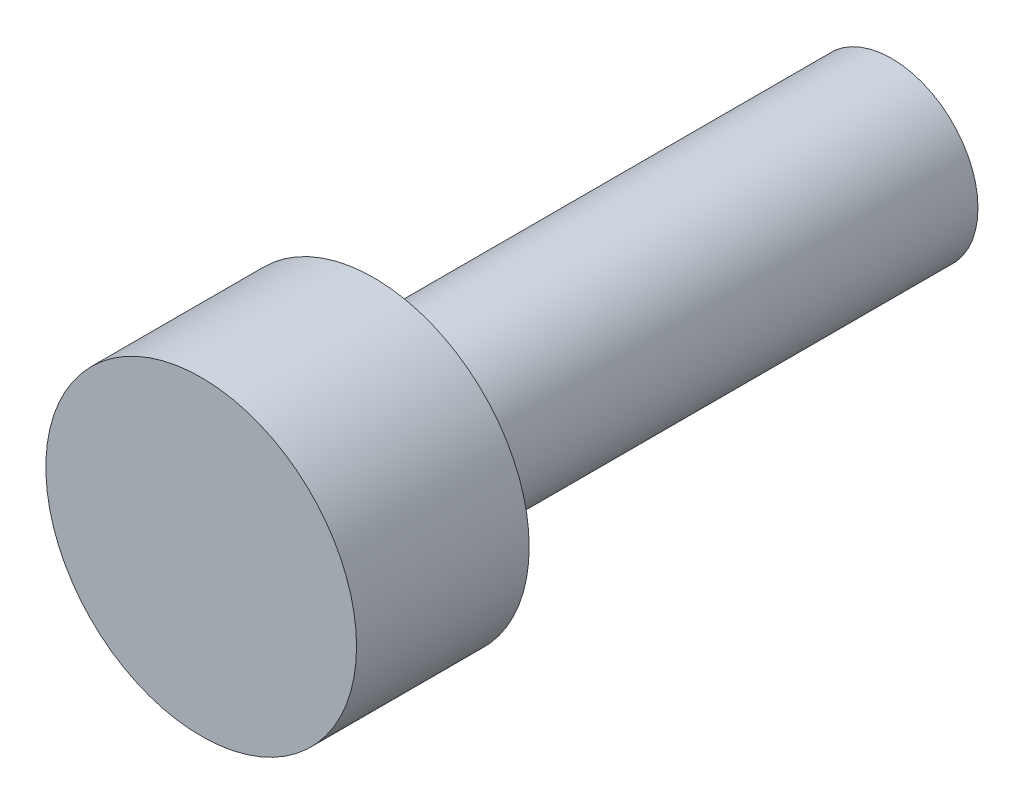
SolidWorks part; units mm, degrees
ref_plane "前视基准面" through (0, 0, 0) normal (0, 0, 1) x (1, 0, 0)
ref_plane "上视基准面" through (0, 0, 0) normal (0, 1, 0) x (1, 0, 0)
ref_plane "右视基准面" through (0, 0, 0) normal (1, 0, 0) x (0, 0, -1)
other "Configuration Table"
sketch "草图1" plane through (0, 0, 0) normal (0, 0, 1) x (1, 0, 0)
  circle A0 centre (0, 0) radius 1
extrude "M2x6简化螺杆" add sketch "草图1" along normal blind 6
sketch "草图2" plane through (0, 0, 0) normal (0, 0, 1) x (1, 0, 0)
  circle A0 centre (0, 0) radius 1.8
extrude "M2简化螺钉头" add sketch "草图2" along normal blind 2 from offset 6
